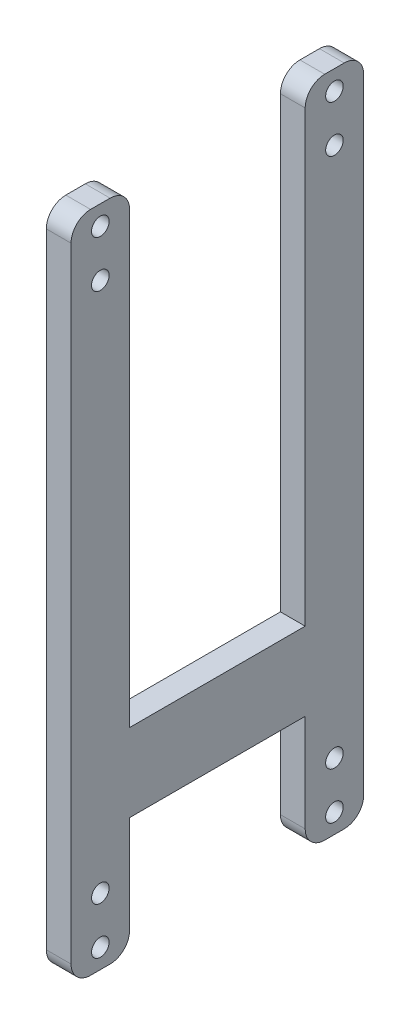
SolidWorks part; units mm, degrees
ref_plane "Alzado" through (0, 0, 0) normal (0, 0, 1) x (1, 0, 0)
ref_plane "Planta" through (0, 0, 0) normal (0, 1, 0) x (1, 0, 0)
ref_plane "Vista lateral" through (0, 0, 0) normal (1, 0, 0) x (0, 0, -1)
sketch "Croquis1" plane through (0, 0, 0) normal (1, 0, 0) x (0, 0, -1)
  line L2 (-22.5, 85) -> (-22.5, -35)
  line L3 (-22.5, -35) -> (22.5, -35)
  line L4 (22.5, -35) -> (22.5, 85)
  line L5 (22.5, 85) -> (37.5, 85)
  line L6 (37.5, 85) -> (37.5, 35)
  line L8 (-37.5, -85) -> (-22.5, -85)
  line L9 (-22.5, -85) -> (-22.5, -55)
  line L10 (-22.5, -55) -> (22.5, -55)
  line L11 (22.5, -55) -> (22.5, -85)
  line L12 (22.5, -85) -> (37.5, -85)
  line L15 (37.5, 35) -> (37.5, -35)
  line L16 (-37.5, 35) -> (-37.5, -35)
  line L21 (-37.5, 85) -> (-37.5, 35)
  line L22 (-37.5, 85) -> (-22.5, 85)
  line L23 (-37.5, -35) -> (-37.5, -85)
  line L26 (37.5, -35) -> (37.5, -85)
  point P1 (37.5, 0)
  point P2 (22.5, -54.8485)
  point P3 (-37.5, -55.1791)
  point P32 (0, -35)
  dimension "D1" = 15
  dimension "D2" = 70
  dimension "D3" = 30
  dimension "D6" = 50
  dimension "D7" = 45
  dimension "D8" = 120
extrude "Saliente-Extruir1" add sketch "Croquis1" along normal blind 6.35
hole_wizard "Taladro de margen para M41" positions "Croquis2" profile "Croquis3" hole size "M4" standard "Ansi Metric" end condition up to next
sketch "Croquis2" plane through (0, 0, 0) normal (-1, 0, 0) x (0, 0, 1)
  line L0 (0, -35) -> (0, 85) construction
  line L1 (-22.5, -35) -> (22.5, -35) construction
  line L3 (22.5, 85) -> (37.5, 85) construction
  line L4 (0, -55) -> (0, -85) construction
  line L5 (22.5, -55) -> (-22.5, -55) construction
  line L7 (22.5, -85) -> (22.5, -55) construction
  line L8 (37.5, -85) -> (22.5, -85) construction
  line L9 (-30, 80) -> (-22.5, 80) construction
  line L10 (-22.5, 85) -> (-22.5, -35) construction
  line L12 (-30, 80) -> (-30, 85) construction
  line L13 (-37.5, 85) -> (-22.5, 85) construction
  line L15 (22.5, -80) -> (30, -80) construction
  line L16 (30, -80) -> (30, -85) construction
  line L19 (30, -80) -> (30, -68) construction
  line L21 (-30, 68) -> (-30, 80) construction
  line L22 (22.5, 85) -> (37.5, 85) construction
  line L23 (22.5, -35) -> (22.5, 85) construction
  point P0 (30, 68)
  point P3 (30, 80)
  point P15 (-30, 68)
  point P16 (-30, 80)
  point P55 (30, -80)
  point P60 (30, -68)
  point P74 (-30, -80)
  point P75 (-30, -68)
  dimension "D1" = 12
  dimension "D2" = 5
  dimension "D3" = 7.5
sketch "Croquis3" plane through (0, 68, 30) normal (0, 1, 0) x (0, 0, 1)
  line L0 (0, 0) -> (0, 6.35)
  line L1 (0, 6.35) -> (2.25, 6.35)
  line L2 (2.25, 6.35) -> (2.25, 0)
  line L5 (2.25, 0) -> (0, 0)
  line L11 (0, -6.35) -> (0, 107.95) construction
  dimension "Diámetro de taladro hasta el siguiente" = 4.5
  dimension "Profundidad de taladro hasta el siguiente" = 6.35
fillet "Redondeo1" radius 5 8 edges at (3.175, -85, -37.5) (3.175, -85, 37.5) (3.175, 85, -37.5) (3.175, 85, 37.5) (3.175, -85, -22.5) (3.175, -85, 22.5) (3.175, 85, -22.5) (3.175, 85, 22.5)
